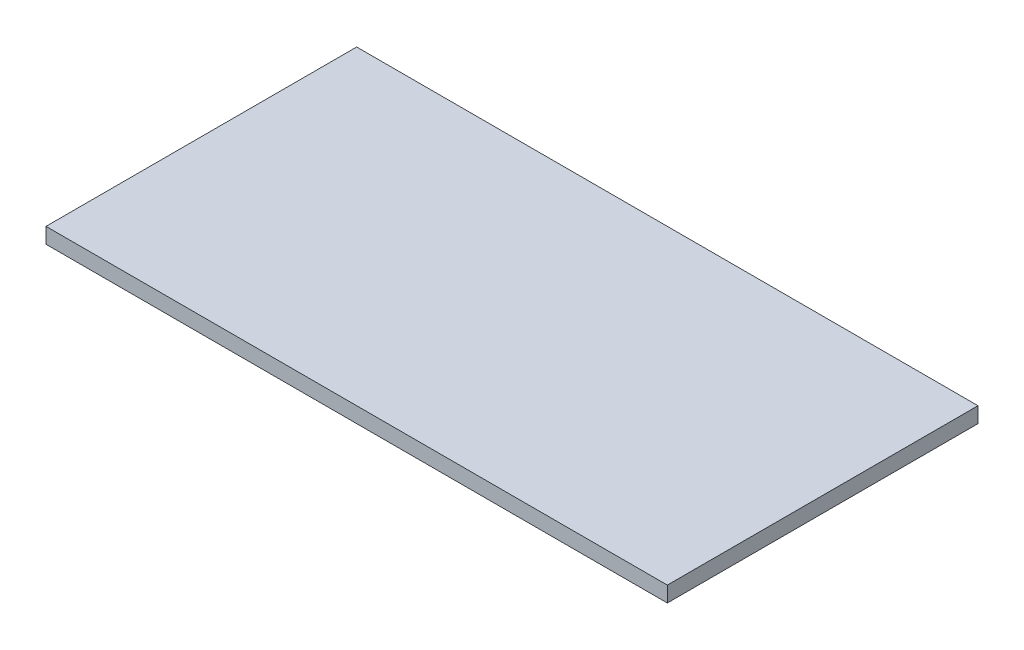
SolidWorks part; units mm, degrees
ref_plane "Front Plane" through (0, 0, 0) normal (0, 0, 1) x (1, 0, 0)
ref_plane "Top Plane" through (0, 0, 0) normal (0, 1, 0) x (1, 0, 0)
ref_plane "Right Plane" through (0, 0, 0) normal (1, 0, 0) x (0, 0, -1)
sketch "Sketch1" plane through (0, 0, 0) normal (0, 1, 0) x (1, 0, 0)
  line L1 (0, 0) -> (1016, 0)
  line L2 (0, 0) -> (0, 508)
  line L3 (0, 508) -> (1016, 508)
  line L4 (1016, 0) -> (1016, 508)
  dimension "D1" = 1016
  dimension "D2" = 508
extrude "Boss-Extrude1" add sketch "Sketch1" along normal blind 25.4
